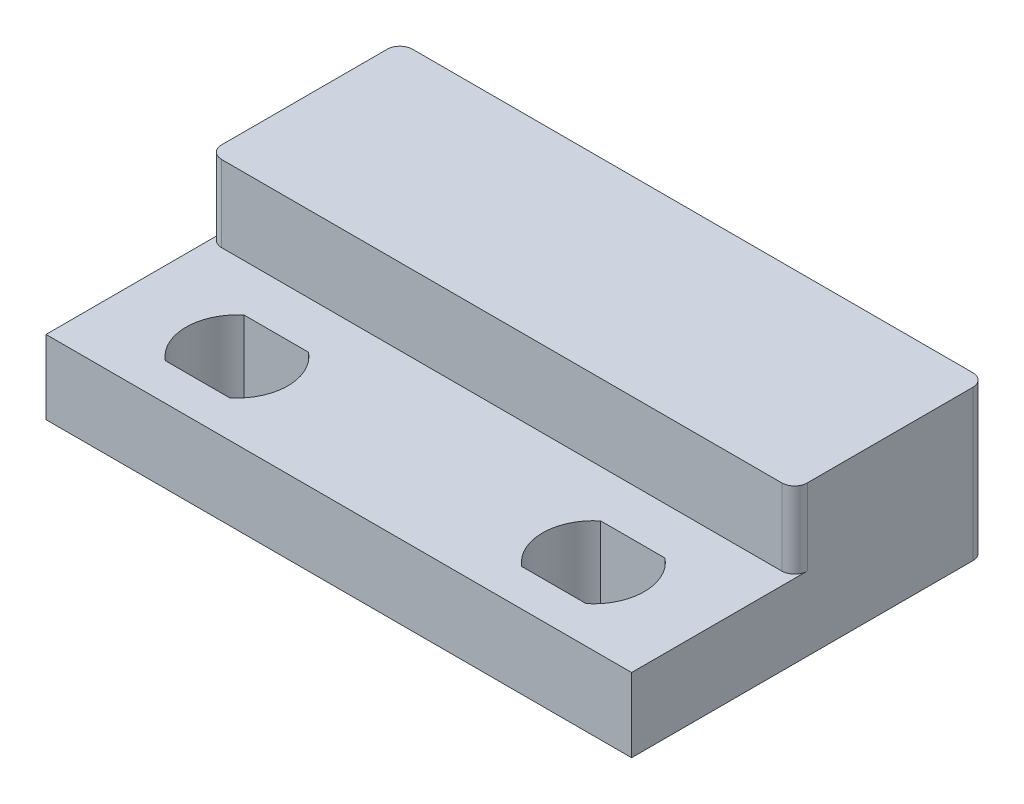
SolidWorks part; units mm, degrees
material "ABS"
ref_plane "Front Plane" through (0, 0, 0) normal (0, 0, 1) x (1, 0, 0)
ref_plane "Top Plane" through (0, 0, 0) normal (0, 1, 0) x (1, 0, 0)
ref_plane "Right Plane" through (0, 0, 0) normal (1, 0, 0) x (0, 0, -1)
sketch "Sketch1" plane through (0, 0, 0) normal (1, 0, 0) x (0, 0, -1)
  line L0 (-10.15, -1.45) -> (3.75, -1.45)
  line L1 (3.75, -1.45) -> (3.75, 4.45)
  line L2 (3.75, 4.45) -> (-3.75, 4.45)
  line L3 (-3.75, 4.45) -> (-3.75, 1.45)
  line L4 (-3.75, 1.45) -> (-10.15, 1.45)
  line L5 (-10.15, 1.45) -> (-10.15, -1.45)
  line L6 (-3.75, 1.45) -> (3.75, -1.45) construction
  dimension "D1" = 5.9
  dimension "D2" = 13.9
  dimension "D3" = 2.9
  dimension "D4" = 6.4
extrude "Boss-Extrude1" add sketch "Sketch1" along normal mid plane 23
sketch "Sketch2" plane through (0, 1.45, 0) normal (0, 1, 0) x (1, 0, 0)
  line L0 (-7, -7.15) -> (7, -7.15) construction
  line L1 (0, 0) -> (0, -7.15) construction
  line L2 (11.5, -10.15) -> (-11.5, -10.15) construction
  line L3 (-8.2639, -5.6) -> (-5.7361, -5.6)
  line L4 (-5.7361, -5.6) -> (0, -5.6) construction
  line L5 (-8.2639, -8.7) -> (-5.7361, -8.7)
  line L6 (5.7361, -5.6) -> (8.2639, -5.6)
  line L7 (0, -5.6) -> (5.7361, -5.6) construction
  line L8 (-5.7361, -8.7) -> (5.7361, -8.7) construction
  line L9 (5.7361, -8.7) -> (8.2639, -8.7)
  arc A0 (-8.2639, -5.6) -> (-8.2639, -8.7) centre (-7, -7.15) ccw
  arc A1 (5.7361, -5.6) -> (5.7361, -8.7) centre (7, -7.15) ccw
  arc A2 (-5.7361, -5.6) -> (-8.2639, -5.6) centre (-7, -7.15) ccw construction
  arc A3 (8.2639, -5.6) -> (5.7361, -5.6) centre (7, -7.15) ccw construction
  arc A4 (-8.2639, -8.7) -> (-5.7361, -8.7) centre (-7, -7.15) ccw construction
  arc A5 (-5.7361, -8.7) -> (-5.7361, -5.6) centre (-7, -7.15) ccw
  arc A6 (5.7361, -8.7) -> (8.2639, -8.7) centre (7, -7.15) ccw construction
  arc A7 (8.2639, -8.7) -> (8.2639, -5.6) centre (7, -7.15) ccw
  point P16 (-5.8625, -5.5049)
  dimension "D1" = 4
  dimension "D2" = 3
  dimension "D3" = 3.1
  dimension "D4" = 14
extrude "Cut-Extrude1" cut sketch "Sketch2" against normal through all
fillet "Fillet1" radius 0.5 4 edges at (11.5, 1.5, -3.75) (11.5, 2.95, 3.75) (-11.5, 1.5, -3.75) (-11.5, 2.95, 3.75)
